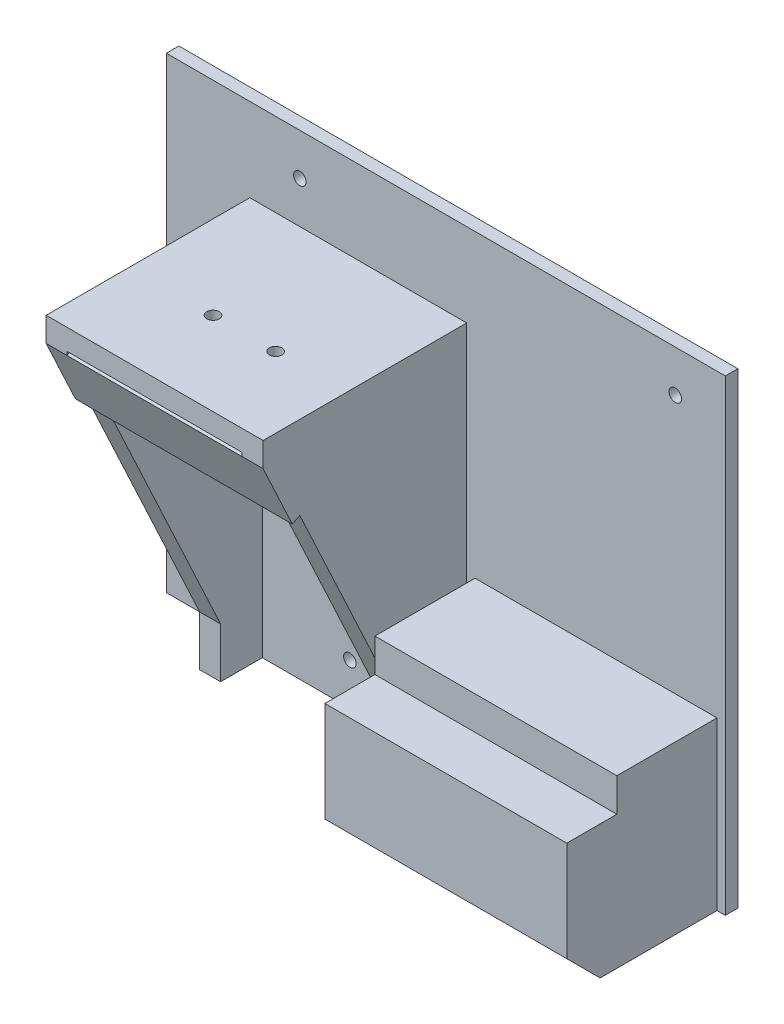
SolidWorks part; units mm, degrees
ref_plane "Alzado" through (0, 0, 0) normal (0, 0, 1) x (1, 0, 0)
ref_plane "Planta" through (0, 0, 0) normal (0, 1, 0) x (1, 0, 0)
ref_plane "Vista lateral" through (0, 0, 0) normal (1, 0, 0) x (0, 0, -1)
sketch "Croquis1" plane through (0, 0, 0) normal (0, 0, 1) x (1, 0, 0)
  line L1 (-67, -56) -> (67, -56)
  line L2 (-67, -56) -> (-67, 56)
  line L3 (-67, 56) -> (67, 56)
  line L4 (67, -56) -> (67, 56)
  line L5 (-67, -56) -> (67, 56) construction
  line L6 (-67, 56) -> (67, -56) construction
  point P0 (0, 0)
  dimension "D1" = 134
  dimension "D2" = 112
extrude "Saliente-Extruir1" add sketch "Croquis1" along normal blind 3
sketch "Croquis2" plane through (0, 0, 3) normal (0, 0, 1) x (1, 0, 0)
  line L0 (-67, -56) -> (67, -56) construction
  line L1 (-47, -56) -> (5, -56)
  line L2 (-47, -56) -> (-47, 36)
  line L3 (-47, 36) -> (5, 36)
  line L4 (5, -56) -> (5, 36)
  line L5 (-67, 56) -> (-67, -56) construction
  dimension "D1" = 20
  dimension "D2" = 92
  dimension "D3" = 52
extrude "Saliente-Extruir2" add sketch "Croquis2" along normal blind 48.812
shell "Vaciado1" thickness 5
sketch "Croquis3" plane through (-47, 0, 0) normal (-1, 0, 0) x (0, 0, 1)
  line L0 (3, -56) -> (15, -56)
  line L1 (51.812, -56) -> (3, -56) construction
  line L2 (15, -56) -> (15, -44)
  line L3 (15, -44) -> (43.0002, 16.0001)
  line L4 (51.812, 36) -> (51.812, 30.154)
  line L5 (51.812, 36) -> (51.812, -56) construction
  line L6 (51.812, 30.154) -> (44.8119, 15.154)
  line L7 (43.0002, 16.0001) -> (44.8119, 15.154)
  line L8 (51.812, 30.154) -> (51.812, -56)
  line L9 (51.812, -56) -> (15, -56)
  line M7 (3, -56) -> (51.812, -56)
  line M8 (51.812, -56) -> (51.812, 36)
  dimension "D1" = 12
  dimension "D2" = 12
  dimension "D3" = 5.846
  dimension "D4" = 16.553
  dimension "D5" = 154.983
  dimension "D6" = 66.212
  dimension "D7" = 154.983
extrude "Cortar-Extruir1" cut sketch "Croquis3" against normal blind 58.812 contours L7 L3 L2 L6 M7 M8
sketch "Croquis4" plane through (-47, 0, 0) normal (-1, 0, 0) x (0, 0, 1)
  line L0 (43.0002, 16.0001) -> (44.8119, 15.154)
  line L1 (44.8119, 15.154) -> (51.812, 30.154)
  line L2 (51.812, 30.154) -> (50.0047, 30.9974)
  line L3 (50.0047, 30.9974) -> (43.0002, 16.0001)
extrude "Saliente-Extruir3" add sketch "Croquis4" against normal blind 48.812
sketch "Croquis5" plane through (0, 0, 3) normal (0, 0, 1) x (1, 0, 0)
  line L0 (5, -56) -> (7, -56)
  line L1 (5, -56) -> (67, -56) construction
  line L2 (7, -56) -> (7, -16)
  line L3 (7, -16) -> (65, -16)
  line L4 (67, -56) -> (67, 56) construction
  line L5 (65, -16) -> (65, -56)
  line L6 (65, -56) -> (7, -56)
  line M9 (5, -56) -> (67, -56)
  dimension "D1" = 2
  dimension "D2" = 40
  dimension "D3" = 2
extrude "Saliente-Extruir4" add sketch "Croquis5" along normal blind 36 contours L5 L3 L2 M9
sketch "Croquis6" plane through (65, 0, 0) normal (1, 0, 0) x (0, 0, -1)
  line L0 (-3, -56) -> (-31, -56)
  line L1 (-39, -56) -> (-3, -56) construction
  line L2 (-31, -56) -> (-39, -47.9996)
  line L3 (-39, -16) -> (-39, -56) construction
  line L4 (-39, -47.9996) -> (-39, -56)
  line L5 (-39, -56) -> (-31, -56)
  line L6 (-39, -47.9996) -> (-39, -23.9996)
  line L7 (-39, -23.9996) -> (-27, -23.9996)
  line L8 (-27, -23.9996) -> (-27, -16)
  line L9 (-39, -16) -> (-3, -16) construction
  line L10 (-27, -16) -> (-39, -16)
  line L11 (-39, -16) -> (-39, -23.9996)
  line M6 (-3, -16) -> (-39, -16)
  line M7 (-39, -16) -> (-39, -56)
  line M8 (-39, -56) -> (-3, -56)
  dimension "D1" = 28
  dimension "D2" = 11.314
  dimension "D3" = 24
  dimension "D4" = 12
extrude "Cortar-Extruir2" cut sketch "Croquis6" against normal blind 58 contours L7 L8 M6 M7 | L2 M8 M7
sketch "Croquis7" plane through (0, 0, 5) normal (0, 0, 1) x (1, 0, 0)
  line L0 (-42, -56) -> (0, -56) construction
  line L1 (-42, 31) -> (-42, -56) construction
  line L2 (67, 56) -> (-67, 56) construction
  line L3 (-67, 56) -> (-67, -56) construction
  circle A0 centre (-21, -46) radius 1.5
  circle A1 centre (-35, 46) radius 1.5
  circle A2 centre (55, 46) radius 1.5
  dimension "D1" = 3
  dimension "D3" = 21
  dimension "D4" = 3
  dimension "D6" = 90
  dimension "D7" = 10
  dimension "D8" = 32
  dimension "D2" = 10
  dimension "D5" = 10
extrude "Cortar-Extruir3" cut sketch "Croquis7" against normal blind 58
sketch "Croquis8" plane through (0, 36, 0) normal (0, 1, 0) x (1, 0, 0)
  line L0 (-47, -51.812) -> (-47, -3) construction
  line L1 (5, -51.812) -> (5, -3) construction
  line L2 (5, -51.812) -> (-47, -51.812) construction
  circle A0 centre (-27, -31.812) radius 1.5
  circle A1 centre (-12, -31.812) radius 1.5
  dimension "D1" = 3
  dimension "D2" = 20
  dimension "D3" = 17
  dimension "D4" = 20
  dimension "D5" = 20
extrude "Cortar-Extruir4" cut sketch "Croquis8" against normal blind 58
